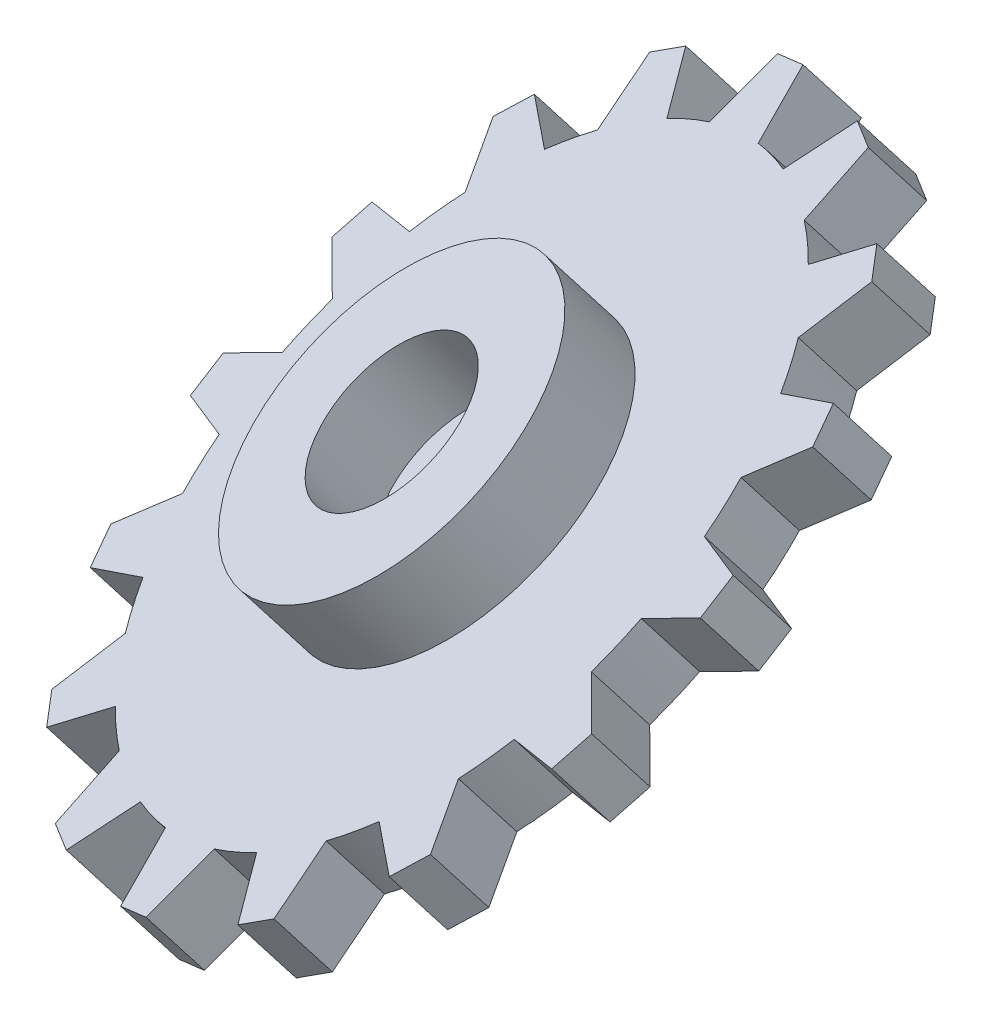
SolidWorks part; units mm, degrees
ref_plane "Front" through (0, 0, 0) normal (0, 0, 1) x (1, 0, 0)
ref_plane "Top" through (0, 0, 0) normal (0, 1, 0) x (1, 0, 0)
ref_plane "Right" through (0, 0, 0) normal (1, 0, 0) x (0, 0, -1)
sketch3d "3DSketch2"
  line L0 (-52.1933, 28.3109, 0) -> (-115.8338, -6.038, 0) construction
ref_plane "Plane2" through (-17.7058, 32.8047, 21.5224) normal (-0.4113, 0.7621, 0.5) x (-0.9115, -0.3439, -0.2256)
sketch "Sketch1" plane through (-35.4116, 65.6093, -43.0448) normal (0.4113, -0.7621, -0.5) x (0.6616, 0.627, -0.4113)
  circle A0 centre (-35.4116, 65.6093) radius 50
  dimension "D1" = 100
extrude "Extrude1" add sketch "Sketch1" along normal blind 10
sketch "Sketch2" plane through (-13.5924, 25.1836, 16.5224) normal (0.4113, -0.7621, -0.5) x (0.6616, 0.627, -0.4113)
  line L0 (0, 0) -> (0, 56.6434) construction
  line L1 (-3, 60) -> (3, 60)
  line L2 (3, 60) -> (8.359, 40)
  line L3 (8.359, 40) -> (-8.359, 40)
  line L4 (-8.359, 40) -> (-3, 60)
  point P5 (0, 40)
  point P8 (0, 60)
  dimension "D1" = 40
  dimension "D2" = 60
  dimension "D3" = 3
  dimension "D4" = 75
extrude "Extrude2" add sketch "Sketch2" against normal blind 10
pattern_circular "CirPattern1" count 16 over 360 about axis through (0, 0, 0) along (-0.4113, 0.7621, 0.5) of "Extrude2"
sketch "Sketch3" plane through (-13.5924, 25.1836, 16.5224) normal (0.4113, -0.7621, -0.5) x (0.6616, 0.627, -0.4113)
  circle A0 centre (0, 0) radius 42.5
  dimension "D1" = 85
extrude "Cut-Extrude1" cut sketch "Sketch3" against normal blind 2
sketch "Sketch4" plane through (-14.4151, 26.7078, 17.5224) normal (0.4113, -0.7621, -0.5) x (0.6616, 0.627, -0.4113)
  circle A0 centre (0, 0) radius 12.5
  circle A1 centre (0, 0) radius 25
  dimension "D1" = 25
  dimension "D2" = 50
extrude "Extrude3" add sketch "Sketch4" along normal blind 10 and the other way blind 20
ref_point "Point1"
